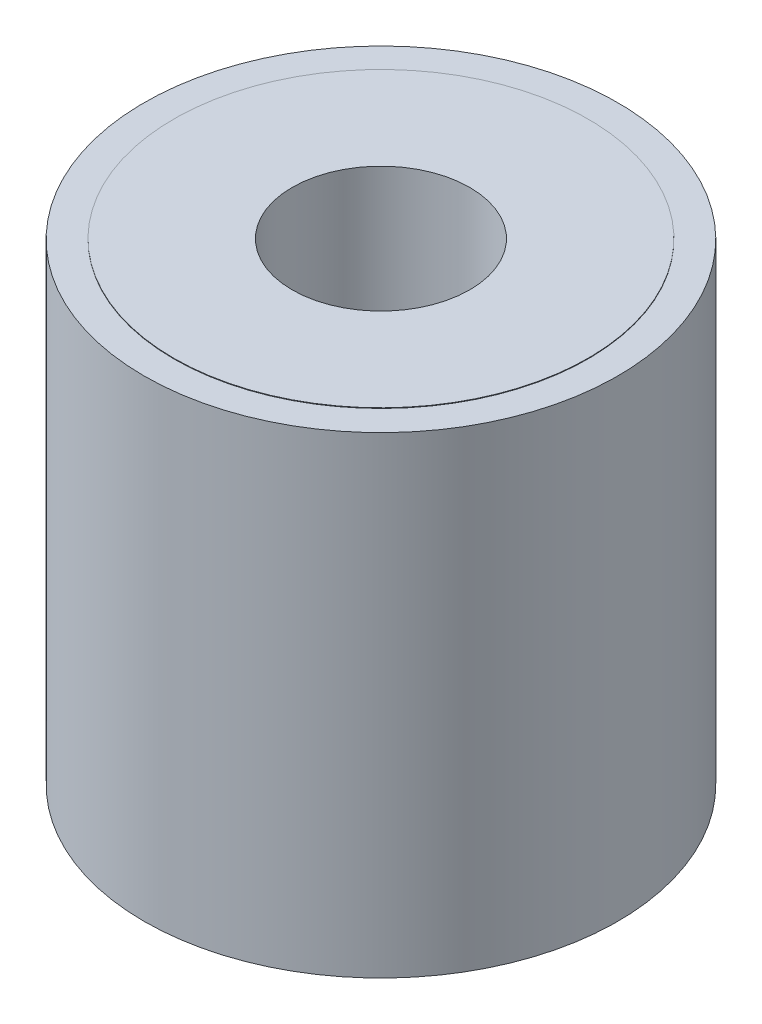
SolidWorks part; units mm, degrees
material "Rubber"
ref_plane "Front Plane" through (0, 0, 0) normal (0, 0, 1) x (1, 0, 0)
ref_plane "Top Plane" through (0, 0, 0) normal (0, 1, 0) x (1, 0, 0)
ref_plane "Right Plane" through (0, 0, 0) normal (1, 0, 0) x (0, 0, -1)
sketch "Sketch1" plane through (0, 0, 0) normal (0, 0, 1) x (1, 0, 0)
  line L0 (0, 1) -> (0, -1) construction
  line L1 (0, -1) -> (-1.5, -1)
  line L2 (-1.5, -1) -> (-1.5, -4)
  line L3 (-1.5, -4) -> (-3.5, -4)
  line L4 (-3.5, -4) -> (-3.5, -3.99)
  line L5 (-3.5, -3.99) -> (-4, -3.99)
  line L6 (-4, -3.99) -> (-4, 3.99)
  line L7 (-4, 3.99) -> (-3.5, 3.99)
  line L8 (-3.5, 3.99) -> (-3.5, 4)
  line L9 (-3.5, 4) -> (-1.5, 4)
  line L10 (-1.5, 4) -> (-1.5, 1)
  line L11 (-1.5, 1) -> (0, 1)
  line L12 (0, -1) -> (0, 1)
  dimension "D1" = 3
  dimension "D2" = 3
  dimension "D3" = 8
  dimension "D4" = 8
  dimension "D5" = 0.01
  dimension "D6" = 0.5
revolve "Revolve1" add sketch "Sketch1" angle 360 about L0
